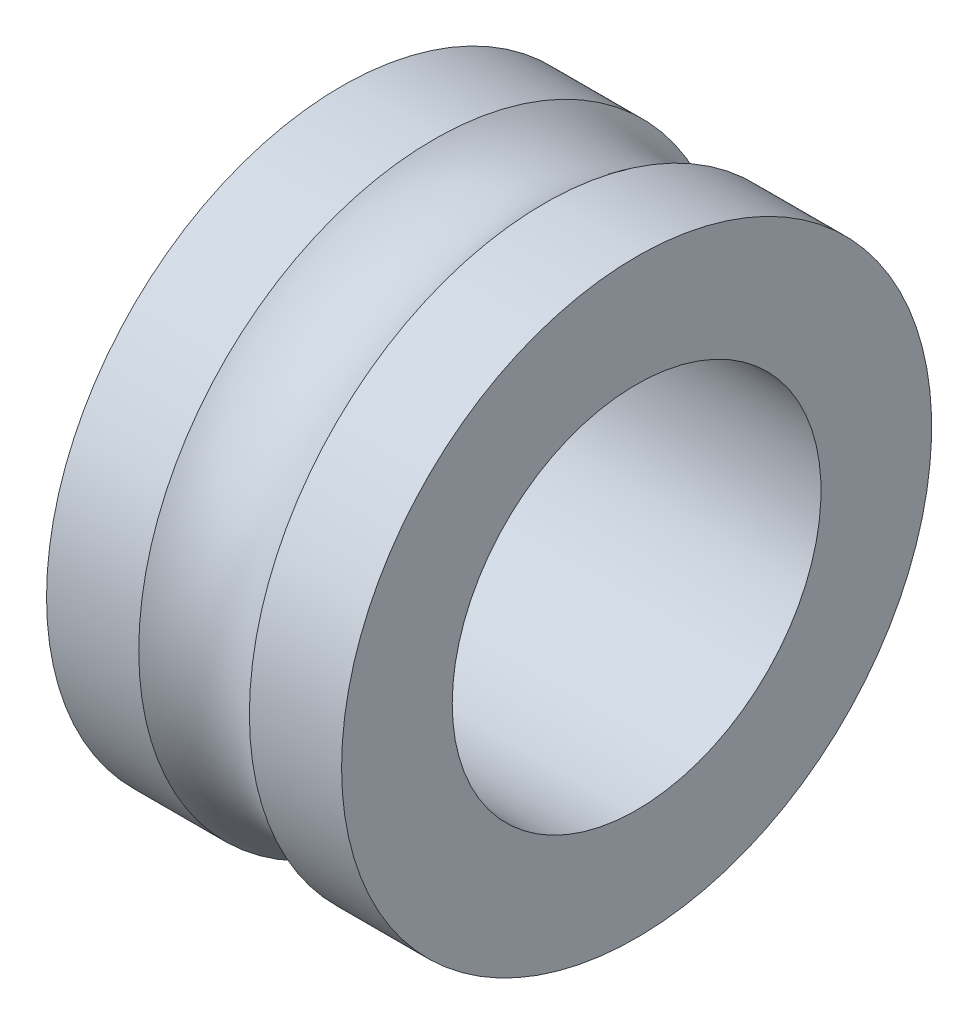
SolidWorks part; units mm, degrees
ref_plane "Plan de face" through (0, 0, 0) normal (0, 0, 1) x (1, 0, 0)
ref_plane "Plan de dessus" through (0, 0, 0) normal (0, 1, 0) x (1, 0, 0)
ref_plane "Plan de droite" through (0, 0, 0) normal (1, 0, 0) x (0, 0, -1)
sketch "Esquisse1" plane through (0, 0, 0) normal (0, 0, 1) x (1, 0, 0)
  line L0 (-1003.746, 10) -> (48996.254, 10) construction
  line L1 (-1.5, 2) -> (1.5, 2) construction
  line L2 (-1.5, 2) -> (-4, 2)
  line L3 (-4, 2) -> (-4, 5)
  line L4 (-4, 5) -> (4, 5)
  line L5 (4, 5) -> (4, 2)
  line L6 (4, 2) -> (1.5, 2)
  circle A0 centre (0, 0) radius 2.5 construction
  arc A1 (-1.5, 2) -> (1.5, 2) centre (0, 0) cw
  dimension "D1" = 5
  dimension "D2" = 5
  dimension "D3" = 3
  dimension "D4" = 10
  dimension "D5" = 8
revolve "Révolution1" add sketch "Esquisse1" angle 360 about L0
